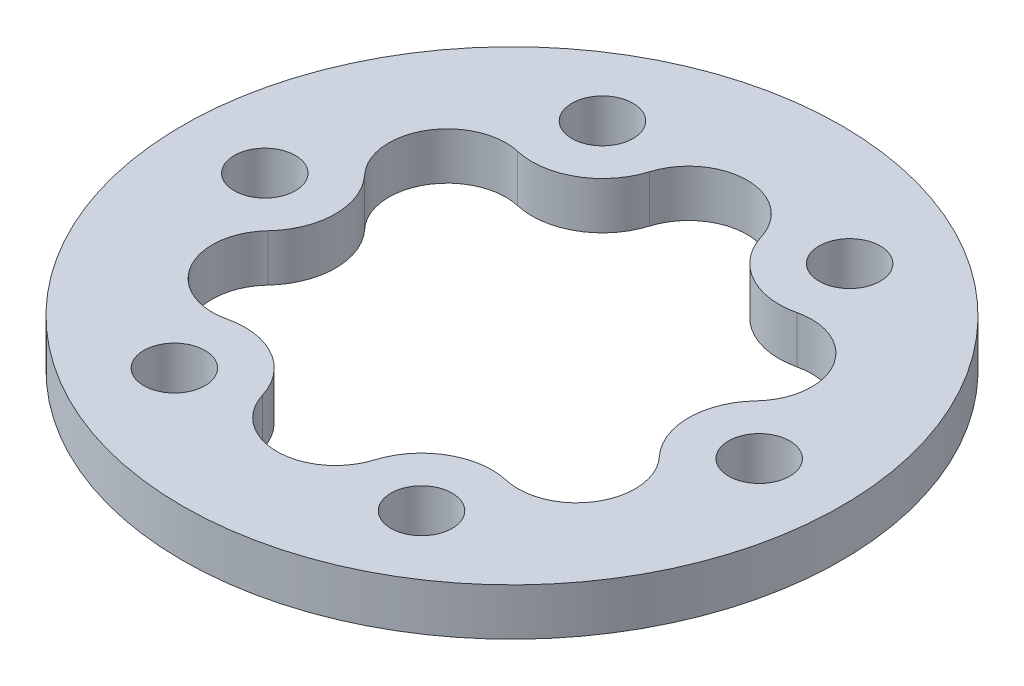
SolidWorks part; units mm, degrees
material "Hexcel AS4C (3000 丝)"
ref_plane "前视基准面" through (0, 0, 0) normal (0, 0, 1) x (1, 0, 0)
ref_plane "上视基准面" through (0, 0, 0) normal (0, 1, 0) x (1, 0, 0)
ref_plane "右视基准面" through (0, 0, 0) normal (1, 0, 0) x (0, 0, -1)
sketch "草图1" plane through (0, 0, 0) normal (0, 1, 0) x (1, 0, 0)
  line L0 (0, 25) -> (0, 0) construction
  line L1 (0, 0) -> (10.5, 18.1865) construction
  circle A0 centre (0, 0) radius 28
  circle A1 centre (0, 0) radius 25 construction
  circle A2 centre (0, 25) radius 1.25 construction
  circle A3 centre (21.6506, 12.5) radius 1.25 construction
  circle A4 centre (21.6506, -12.5) radius 1.25 construction
  circle A5 centre (0, -25) radius 1.25 construction
  circle A6 centre (-21.6506, -12.5) radius 1.25 construction
  circle A7 centre (-21.6506, 12.5) radius 1.25 construction
  circle A8 centre (0, 0) radius 15 construction
  circle A9 centre (0, 15) radius 4 construction
  circle A10 centre (12.9904, -7.5) radius 4 construction
  circle A11 centre (-12.9904, -7.5) radius 4 construction
  circle A12 centre (0, 0) radius 21 construction
  circle A13 centre (10.5, 18.1865) radius 2.6
  circle A14 centre (21, 0) radius 2.6
  circle A15 centre (10.5, -18.1865) radius 2.6
  circle A16 centre (-10.5, -18.1865) radius 2.6
  circle A17 centre (-21, 0) radius 2.6
  circle A18 centre (-10.5, 18.1865) radius 2.6
  dimension "D1" = 2.5
  dimension "D2" = 50
  dimension "D3" = 56
  dimension "D5" = 30
  dimension "D6" = 8
  dimension "D9" = 5.2
  dimension "D10" = 42
  dimension "D8" = 30
  dimension "D4" = 6
  dimension "D7" = 3
  dimension "D11" = 6
extrude "凸台-拉伸1" add sketch "草图1" along normal blind 4
sketch "草图4" plane through (0, 4, 0) normal (0, 1, 0) x (1, 0, 0)
  circle A0 centre (0, 0) radius 15 construction
  circle A1 centre (0, 15) radius 4 construction
  circle A2 centre (12.9904, 7.5) radius 4 construction
  circle A3 centre (12.9904, -7.5) radius 4 construction
  circle A4 centre (0, -15) radius 4 construction
  circle A5 centre (-12.9904, -7.5) radius 4 construction
  circle A6 centre (-12.9904, 7.5) radius 4 construction
  arc A7 (4.7586, 16.4441) -> (11.8617, 12.3431) centre (10.5, 18.1865) ccw
  arc A8 (-4.7586, 16.4441) -> (4.7586, 16.4441) centre (0, 15) cw
  arc A9 (11.8617, 12.3431) -> (16.6203, 4.101) centre (12.9904, 7.5) cw
  arc A10 (16.6203, 4.101) -> (16.6203, -4.101) centre (21, 0) ccw
  arc A11 (16.6203, -4.101) -> (11.8617, -12.3431) centre (12.9904, -7.5) cw
  arc A12 (11.8617, -12.3431) -> (4.7586, -16.4441) centre (10.5, -18.1865) ccw
  arc A13 (4.7586, -16.4441) -> (-4.7586, -16.4441) centre (0, -15) cw
  arc A14 (-4.7586, -16.4441) -> (-11.8617, -12.3431) centre (-10.5, -18.1865) ccw
  arc A15 (-11.8617, -12.3431) -> (-16.6203, -4.101) centre (-12.9904, -7.5) cw
  arc A16 (-16.6203, -4.101) -> (-16.6203, 4.101) centre (-21, 0) ccw
  arc A17 (-16.6203, 4.101) -> (-11.8617, 12.3431) centre (-12.9904, 7.5) cw
  arc A18 (-11.8617, 12.3431) -> (-4.7586, 16.4441) centre (-10.5, 18.1865) ccw
  dimension "D1" = 30
  dimension "D2" = 8
  dimension "D4" = 6
  dimension "D3" = 6
  dimension "D5" = 6
extrude "切除-拉伸2" cut sketch "草图4" against normal through all and the other way through all
move or copy body "实体-移动/复制1" bodies to move or copy 109 parameters "D1"=0, "D2"=0, "D3"=0
